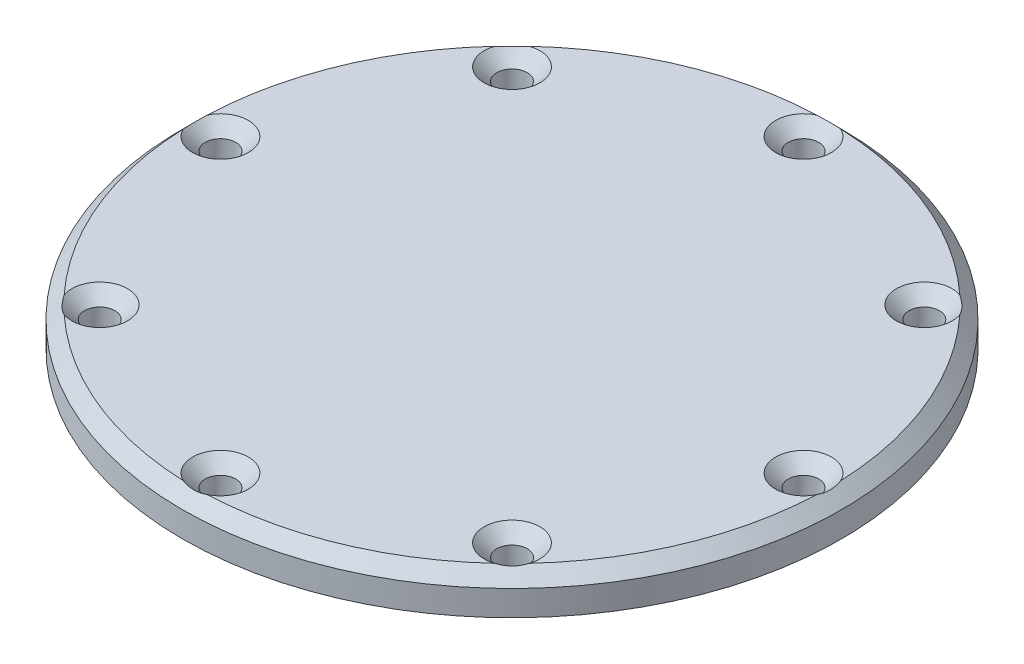
SolidWorks part; units mm, degrees
ref_plane "Спереди" through (0, 0, 0) normal (0, 0, 1) x (1, 0, 0)
ref_plane "Сверху" through (0, 0, 0) normal (0, 1, 0) x (1, 0, 0)
ref_plane "Справа" through (0, 0, 0) normal (1, 0, 0) x (0, 0, -1)
sketch "Эскиз1" plane through (0, 0, 0) normal (0, 0, 1) x (1, 0, 0)
  line L0 (0, 0) -> (0, 14224.778) construction
  line L1 (0, 0) -> (26, 0)
  line L2 (26, 0) -> (26, 2)
  line L3 (26, 2) -> (25, 3)
  line L4 (25, 3) -> (0, 3)
  line L5 (0, 3) -> (0, 0)
  dimension "D1" = 3
  dimension "D2" = 52
  dimension "D3" = 1
  dimension "D4" = 45
revolve "Повернуть1" add sketch "Эскиз1" angle 360 about L0
hole_wizard "Зенковка для винта с потайной головкой M21" positions "Эскиз2" profile "Эскиз3" countersink size "M2" standard "HASCO Metric" end condition through all
sketch "Эскиз2" plane through (0, 3, 0) normal (0, 1, 0) x (1, 0, 0)
  line L2 (0, 0) -> (18.3848, 18.3848) construction
  line L4 (0, 0) -> (0, 26) construction
  circle A1 centre (0, 0) radius 26 construction
  circle A2 centre (0, 0) radius 23 construction
  point P0 (16.2635, 16.2635)
  dimension "D2" = 46
  dimension "D1" = 45
sketch "Эскиз3" plane through (16.2635, 3, -16.2635) normal (1, 0, 0) x (0, 0, 1)
  line L0 (0, 0) -> (0, 3)
  line L1 (0, 3) -> (1.2, 3)
  line L2 (1.2, 3) -> (1.2, 1)
  line L3 (1.2, 1) -> (2.2, 0)
  line L5 (2.2, 0) -> (0, 0)
  line L6 (-1.2, 1) -> (-2.2, 0) construction
  line L11 (0, -6.35) -> (0, 107.95) construction
  dimension "Диаметр сквозного отверстия" = 2.4
  dimension "Глубина сквозного отверстия" = 3
  dimension "Диаметр передней зенковки" = 4.4
  dimension "Угол передней зенковки" = 90
pattern_circular "Круговой массив1" count 8 over 360 about axis through (0, 0, 0) along (0, 1, 0) of "Зенковка для винта с потайной головкой M21"
